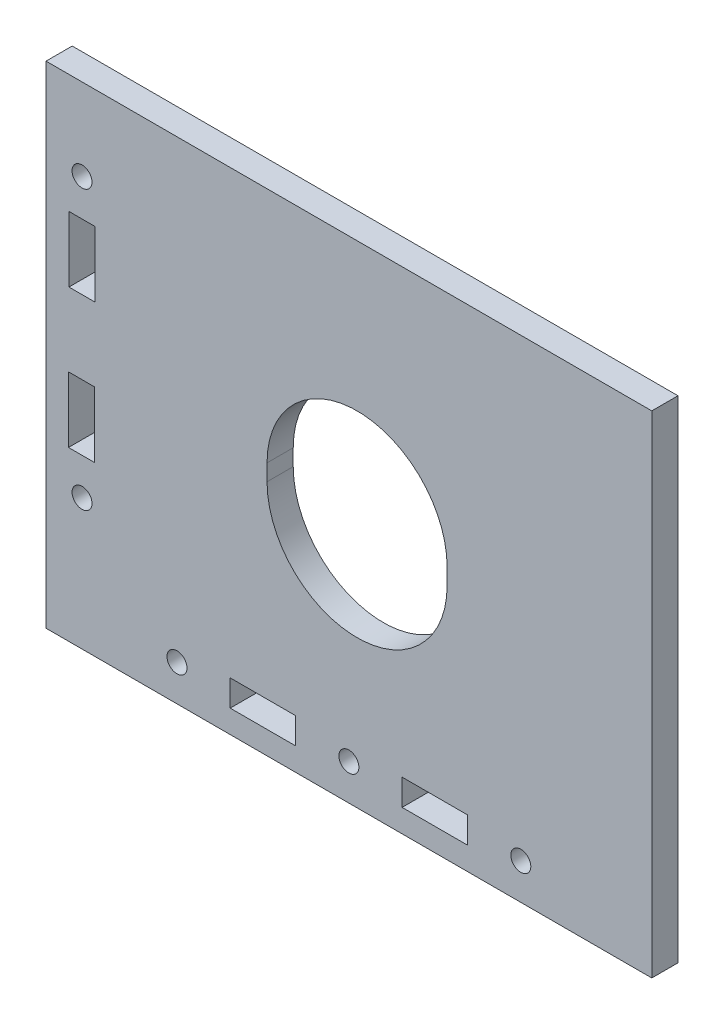
SolidWorks part; units mm, degrees
ref_plane "Front Plane" through (0, 0, 0) normal (0, 0, 1) x (1, 0, 0)
ref_plane "Top Plane" through (0, 0, 0) normal (0, 1, 0) x (1, 0, 0)
ref_plane "Right Plane" through (0, 0, 0) normal (1, 0, 0) x (0, 0, -1)
sketch "Model" plane through (0, 0, 0) normal (0, 0, 1) x (1, 0, 0)
  line L1 (170, -15) -> (170, 135)
  line L3 (-15, -15) -> (-15, 135)
  line L8 (170, 135) -> (-15, 135)
  line L10 (170, -15) -> (-15, -15)
  line L11 (93.75, -8) -> (93.75, 0)
  line L12 (93.75, 0) -> (113.75, 0)
  line L13 (113.75, 0) -> (113.75, -8)
  line L14 (113.75, -8) -> (93.75, -8)
  line L15 (52.5, 57.5) -> (52.5, 62.5)
  line L16 (107.5, 62.5) -> (107.5, 57.5)
  line L17 (41.25, -8) -> (41.25, 0)
  line L18 (41.25, 0) -> (61.25, 0)
  line L19 (61.25, 0) -> (61.25, -8)
  line L20 (61.25, -8) -> (41.25, -8)
  line L21 (-8, 78.75) -> (-8, 98.75)
  line L22 (-8, 98.75) -> (0, 98.75)
  line L23 (0, 98.75) -> (0, 78.75)
  line L24 (0, 78.75) -> (-8, 78.75)
  line L25 (-8.1347, 36.25) -> (-8.1347, 56.25)
  line L26 (-8.1347, 56.25) -> (-0.1347, 56.25)
  line L27 (-0.1347, 56.25) -> (-0.1347, 36.25)
  line L28 (-0.1347, 36.25) -> (-8.1347, 36.25)
  arc A11 (107.5, 62.5) -> (52.5, 62.5) centre (80, 62.5) ccw
  arc A12 (52.5, 57.5) -> (107.5, 57.5) centre (80, 57.5) ccw
  circle A14 centre (130, -4) radius 3.05
  circle A15 centre (25, -4) radius 3.05
  circle A16 centre (-4, 25) radius 3.05
  circle A17 centre (-4, 110) radius 3.05
  circle A18 centre (77.5, -4) radius 3.05
extrude "Boss-Extrude1" add sketch "Model" along normal blind 8
